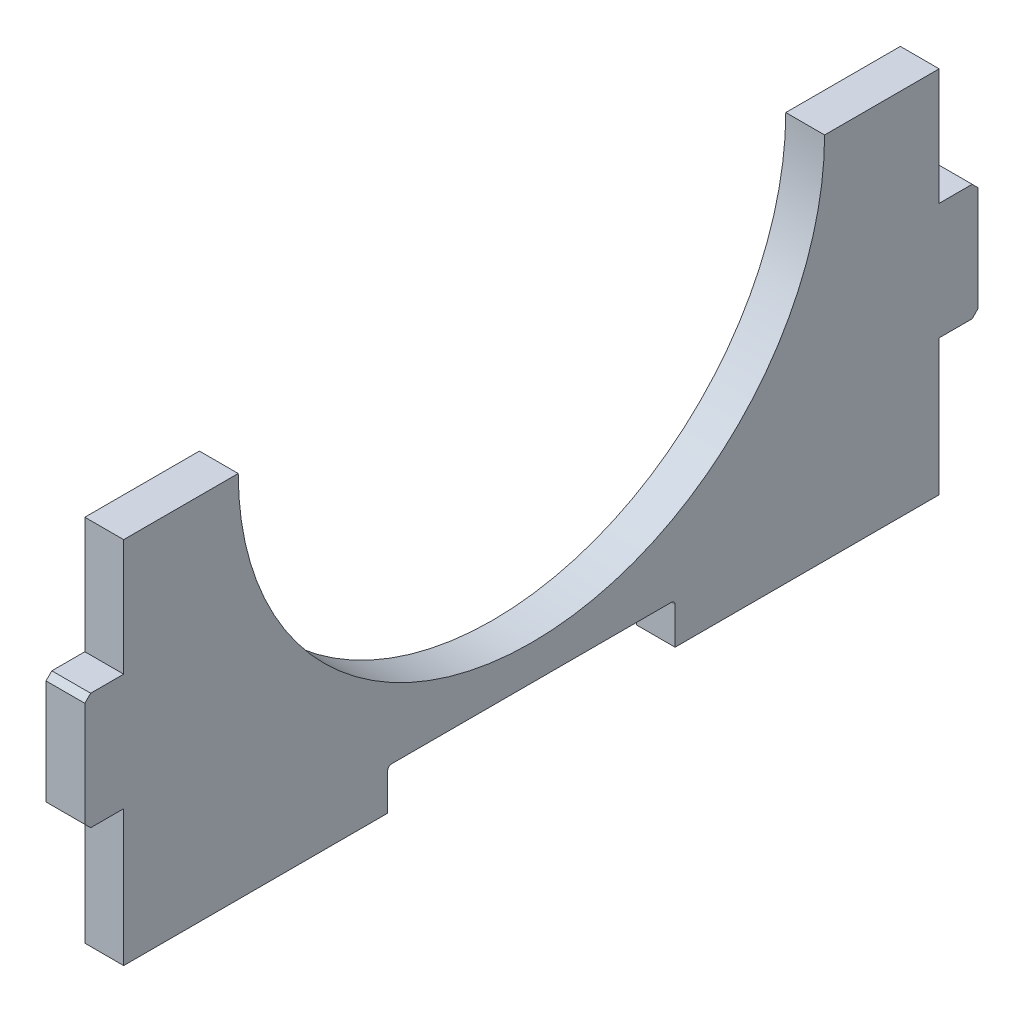
SolidWorks part; units mm, degrees
material "未指定"
ref_plane "正面" through (0, 0, 0) normal (0, 0, 1) x (1, 0, 0)
ref_plane "平面" through (0, 0, 0) normal (0, 1, 0) x (1, 0, 0)
ref_plane "右側面" through (0, 0, 0) normal (1, 0, 0) x (0, 0, -1)
sketch "ｽｹｯﾁ1" plane through (0, 0, 0) normal (1, 0, 0) x (0, 0, -1)
  line L0 (75.5, 0) -> (105, 0)
  line L1 (105, 0) -> (105, -95)
  line L2 (105, -95) -> (-105, -95)
  line L3 (-105, -95) -> (-105, 0)
  line L4 (-105, 0) -> (-75.5, 0)
  line L5 (0, 0) -> (0, 25) construction
  arc A0 (75.5, 0) -> (-75.5, 0) centre (0, 0) cw
  dimension "D3" = 75.5
  dimension "D1" = 210
  dimension "D2" = 95
extrude "板 外形切り出し" add sketch "ｽｹｯﾁ1" along normal mid plane 10
sketch "ｽｹｯﾁ2" plane through (0, 0, 0) normal (1, 0, 0) x (0, 0, -1)
  line L0 (-105, -60) -> (-115, -60)
  line L1 (-115, -60) -> (-115, -30)
  line L2 (-115, -30) -> (-105, -30)
  line L3 (-105, -30) -> (-105, -60)
  dimension "D1" = 115
  dimension "D2" = 105
  dimension "D3" = 60
  dimension "D4" = 30
extrude "ほぞ(右)" add sketch "ｽｹｯﾁ2" along normal mid plane 10
chamfer "ほぞ(右) 先端面取り" distance 1.5 angle 45 2 edges at (0, -30, 115) (0, -60, 115)
mirror "ほぞ(左)" about plane through (0, 0, 0) normal (0, 0, 1) of "ほぞ(右) 先端面取り", "ほぞ(右)"
sketch "ｽｹｯﾁ3" plane through (0, 0, 0) normal (1, 0, 0) x (0, 0, -1)
  line L0 (37, -95) -> (-37, -95)
  line L1 (-37, -95) -> (-37, -84.5)
  line L2 (-37, -84.5) -> (37, -84.5)
  line L3 (37, -84.5) -> (37, -95)
  line L4 (0, 0) -> (0, 25) construction
  dimension "D2" = 95
  dimension "D1" = 74
  dimension "D3" = 84.5
extrude "くぐり穴" cut sketch "ｽｹｯﾁ3" against normal through all and the other way through all
fillet "くぐり穴 内角R" radius 1 2 edges at (0, -84.5, 37) (0, -84.5, -37)
equation "\"INNER_HALF_W\" = 105"
equation "\"D1@ｽｹｯﾁ1\" = 2 * ( \"INNER_HALF_W\" )"
equation "\"DECK_TOP\" = -95"
equation "\"D2@ｽｹｯﾁ1\" = abs( \"DECK_TOP\" )"
equation "\"CRADLE_BORE\" = 151"
equation "\"D3@ｽｹｯﾁ1\" = \"CRADLE_BORE\" / 2"
equation "\"PLATE_T\" = 10"
equation "\"D1@板 外形切り出し\" = \"PLATE_T\""
equation "\"D1@ｽｹｯﾁ2\" = \"INNER_HALF_W\" + \"PLATE_T\""
equation "\"D2@ｽｹｯﾁ2\" = \"INNER_HALF_W\""
equation "\"TAB_Y\" = 45"
equation "\"TAB_W\" = 30"
equation "\"D3@ｽｹｯﾁ2\" = abs( -\"TAB_Y\" - \"TAB_W\" / 2 )"
equation "\"D4@ｽｹｯﾁ2\" = abs( -\"TAB_Y\" + \"TAB_W\" / 2 )"
equation "\"D1@ほぞ(右)\" = \"PLATE_T\""
equation "\"TAB_C\" = 1.5"
equation "\"D1@ほぞ(右) 先端面取り\" = \"TAB_C\""
equation "\"NOTCH_W\" = 37"
equation "\"D1@ｽｹｯﾁ3\" = 2 * ( \"NOTCH_W\" )"
equation "\"D2@ｽｹｯﾁ3\" = abs( \"DECK_TOP\" )"
equation "\"NOTCH_H\" = 10.5"
equation "\"D3@ｽｹｯﾁ3\" = abs( \"DECK_TOP\" + \"NOTCH_H\" )"
equation "\"CUT_R\" = 1"
equation "\"D1@くぐり穴 内角R\" = \"CUT_R\""
